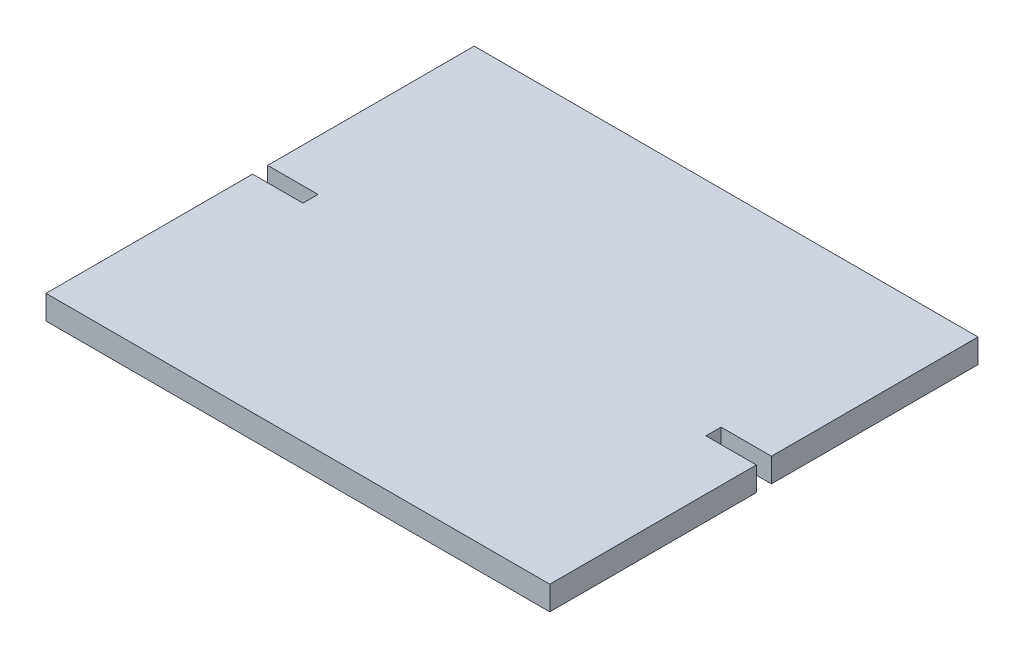
SolidWorks part; units mm, degrees
material "Hardboard"
ref_plane "Front Plane" through (0, 0, 0) normal (0, 0, 1) x (1, 0, 0)
ref_plane "Top Plane" through (0, 0, 0) normal (0, 1, 0) x (1, 0, 0)
ref_plane "Right Plane" through (0, 0, 0) normal (1, 0, 0) x (0, 0, -1)
sketch "Sketch3" plane through (0, 0, 0) normal (0, 1, 0) x (1, 0, 0)
  line L0 (0, -42.5) -> (0, 42.5) construction
  line L1 (-50, -42.5) -> (50, -42.5)
  line L2 (-50, 42.5) -> (-50, 1.5)
  line L3 (-50, 42.5) -> (50, 42.5)
  line L4 (40, 1.5) -> (40, -1.5)
  line L5 (-50, -42.5) -> (50, 42.5) construction
  line L6 (-50, 42.5) -> (50, -42.5) construction
  line L7 (-50, 1.5) -> (-40, 1.5)
  line L8 (-50, -1.5) -> (-50, -42.5)
  line L9 (-50, -1.5) -> (-40, -1.5)
  line L10 (-40, 1.5) -> (-40, -1.5)
  line L11 (50, -1.5) -> (40, -1.5)
  line L12 (50, -1.5) -> (50, -42.5)
  line L13 (50, 1.5) -> (40, 1.5)
  line L14 (50, 42.5) -> (50, 1.5)
  line L15 (-50, -1.5) -> (-50, 1.5) construction
  point P0 (0, 0)
  point P16 (-50, 0)
  point P17 (50, 0)
  point P18 (-1000, 0)
  point P19 (1000, 0)
  dimension "D1" = 85
  dimension "D2" = 100
  dimension "D3" = 3
  dimension "D4" = 10
  dimension "D5" = 1000
extrude "Boss-Extrude1" add sketch "Sketch3" against normal blind 4.7625
sketch "Sketch4" [suppressed] plane through (0, 0, 0) normal (1, 0, 0) x (0, 0, -1)
  line L0 (-30, 4.7625) -> (-1.5, 4.7625) construction
  line L1 (-30, 4.7625) -> (-30, 0) construction
  line L2 (-30, 0) -> (-1.5, 0) construction
  line L3 (-30, 4.7625) -> (-1.5, 4.7625)
  line L4 (-30, 4.7625) -> (-30, 0)
  line L5 (-30, 0) -> (-1.5, 0)
  line L6 (-30, 4.7625) -> (-30, -12.1326)
  line L7 (-30, -12.1326) -> (-9.7945, -32.8109)
  line L9 (-9.7945, -32.8109) -> (-7.1756, -30.2519)
  line L11 (-7.1756, -30.2519) -> (-24.8806, -12.1326)
  line L12 (-24.8806, -12.1326) -> (-24.8806, 4.7625)
  line L13 (-24.8806, 4.7625) -> (-30, 4.7625)
